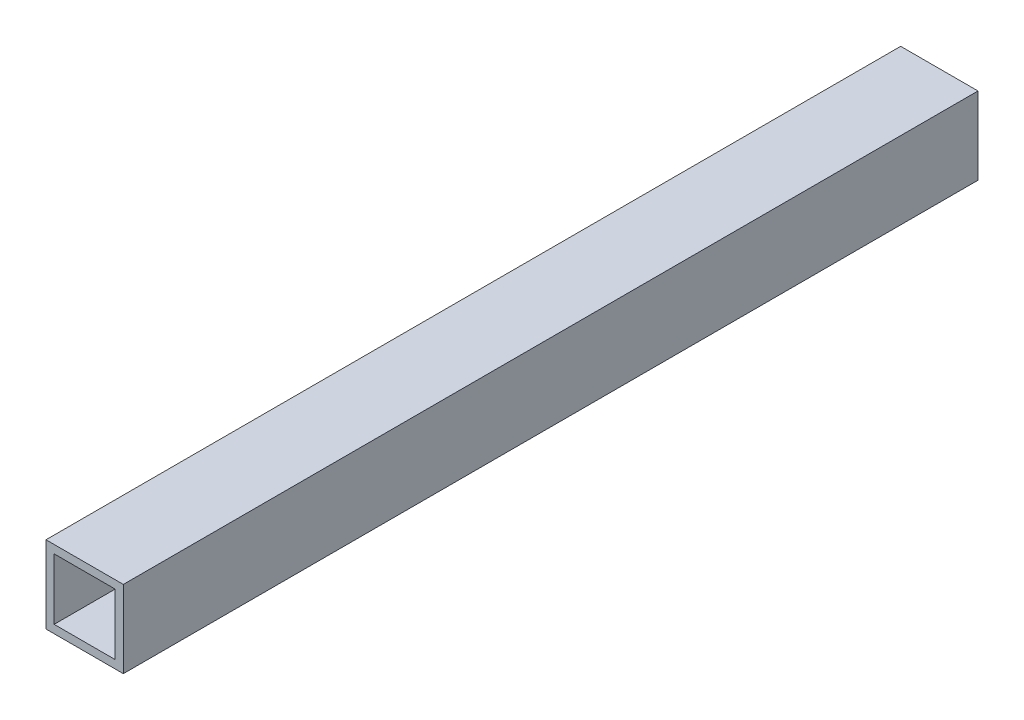
SolidWorks part; units mm, degrees
material "1060 Alloy"
ref_plane "Front Plane" through (0, 0, 0) normal (0, 0, 1) x (1, 0, 0)
ref_plane "Top Plane" through (0, 0, 0) normal (0, 1, 0) x (1, 0, 0)
ref_plane "Right Plane" through (0, 0, 0) normal (1, 0, 0) x (0, 0, -1)
sketch "Sketch1" plane through (0, 0, 0) normal (0, 0, 1) x (1, 0, 0)
  line L0 (-7.5, 7.5) -> (7.5, 7.5)
  line L1 (-9.5, -9.5) -> (9.5, -9.5)
  line L2 (-9.5, -9.5) -> (-9.5, 9.5)
  line L3 (-9.5, 9.5) -> (9.5, 9.5)
  line L4 (9.5, -9.5) -> (9.5, 9.5)
  line L5 (-9.5, -9.5) -> (9.5, 9.5) construction
  line L6 (-9.5, 9.5) -> (9.5, -9.5) construction
  line L7 (7.5, -7.5) -> (7.5, 7.5)
  line L8 (-7.5, -7.5) -> (7.5, -7.5)
  line L9 (-7.5, -7.5) -> (-7.5, 7.5)
  point P0 (0, 0)
  dimension "D2" = 19
  dimension "D3" = 19
  dimension "D1" = 2
extrude "Boss-Extrude1" add sketch "Sketch1" along normal blind 210
